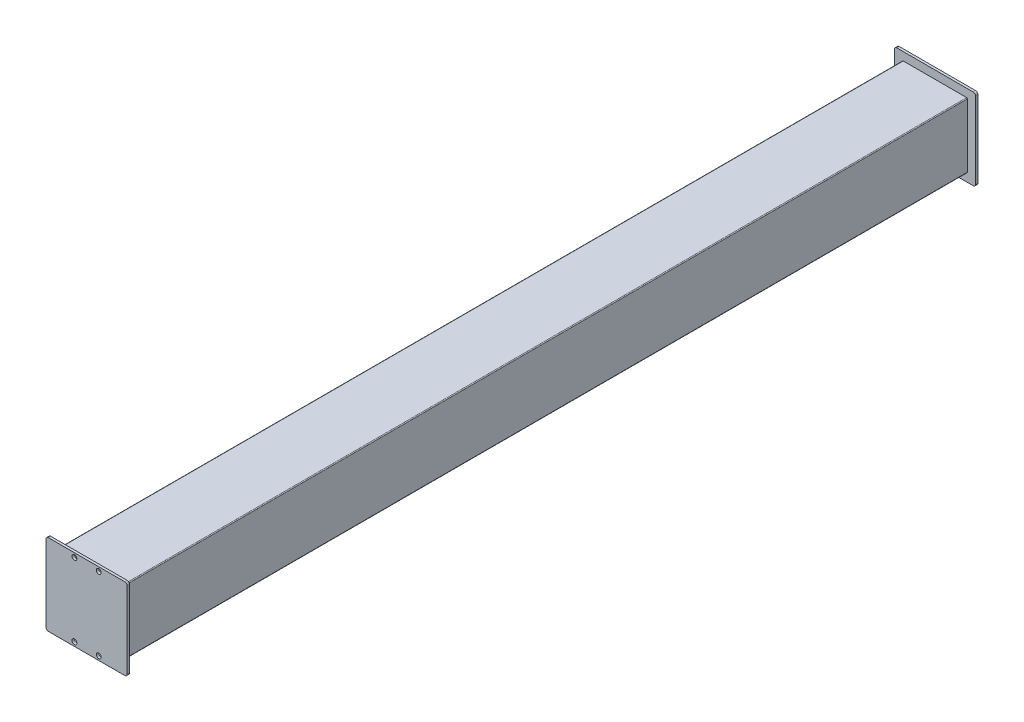
SolidWorks part; units mm, degrees
material "Alloy Steel"
ref_plane "Front Plane" through (0, 0, 0) normal (0, 0, 1) x (1, 0, 0)
ref_plane "Top Plane" through (0, 0, 0) normal (0, 1, 0) x (1, 0, 0)
ref_plane "Right Plane" through (0, 0, 0) normal (1, 0, 0) x (0, 0, -1)
sketch "Sketch2" plane through (0, 0, 0) normal (0, 0, 1) x (1, 0, 0)
  line L0 (-36.4, 36.4) -> (36.4, 36.4)
  line L1 (-40, -40) -> (40, -40)
  line L2 (-40, -40) -> (-40, 40)
  line L3 (-40, 40) -> (40, 40)
  line L4 (40, -40) -> (40, 40)
  line L5 (-40, -40) -> (40, 40) construction
  line L6 (-40, 40) -> (40, -40) construction
  line L7 (36.4, -36.4) -> (36.4, 36.4)
  line L8 (-36.4, -36.4) -> (36.4, -36.4)
  line L9 (-36.4, -36.4) -> (-36.4, 36.4)
  point P0 (0, 0)
  dimension "D1" = 80
  dimension "D2" = 80
  dimension "D3" = 3.6
extrude "Boss-Extrude1" add sketch "Sketch2" along normal blind 1042
fillet "Fillet1" radius 1 4 edges at (40, -40, 521) (-40, -40, 521) (40, 40, 521) (-40, 40, 521)
fillet "Fillet2" radius 1 4 edges at (36.4, -36.4, 521) (-36.4, -36.4, 521) (-36.4, 36.4, 521) (36.4, 36.4, 521)
sketch "Sketch3" plane through (0, 0, 1042) normal (0, 0, 1) x (1, 0, 0)
  line L1 (-50, -50) -> (50, -50)
  line L2 (-50, -50) -> (-50, 50)
  line L3 (-50, 50) -> (50, 50)
  line L4 (50, -50) -> (50, 50)
  line L5 (-50, -50) -> (50, 50) construction
  line L6 (-50, 50) -> (50, -50) construction
  point P0 (0, 0)
  dimension "D1" = 100
  dimension "D2" = 100
extrude "Boss-Extrude2" add sketch "Sketch3" along normal blind 3
fillet "Fillet3" radius 3 4 edges at (-50, -50, 1043.5) (50, -50, 1043.5) (50, 50, 1043.5) (-50, 50, 1043.5)
sketch "Sketch5" plane through (0, 0, 1042) normal (0, 0, -1) x (-1, 0, 0)
  line L0 (0, -50) -> (0, 50) construction
  line L1 (47, -50) -> (-47, -50) construction
  line L2 (-47, 50) -> (47, 50) construction
  line L3 (-50, 0) -> (50, 0) construction
  line L4 (-50, -47) -> (-50, 47) construction
  line L5 (50, 47) -> (50, -47) construction
  circle A0 centre (15, -45) radius 3
  circle A1 centre (-15, -45) radius 3
  circle A2 centre (15, 45) radius 3
  circle A3 centre (-15, 45) radius 3
  dimension "D1" = 5
  dimension "D2" = 5
  dimension "D3" = 6
  dimension "D4" = 15
  dimension "D5" = 15
extrude "Cut-Extrude1" cut sketch "Sketch5" against normal up to surface (3 mm away) up to face at (0, 0, 1045)
sketch "Sketch6" plane through (0, 0, 0) normal (0, 0, -1) x (-1, 0, 0)
  line L1 (-50, -50) -> (50, -50)
  line L2 (-50, -50) -> (-50, 50)
  line L3 (-50, 50) -> (50, 50)
  line L4 (50, -50) -> (50, 50)
  line L5 (-50, -50) -> (50, 50) construction
  line L6 (-50, 50) -> (50, -50) construction
  point P0 (0, 0)
  dimension "D1" = 100
  dimension "D2" = 100
extrude "Boss-Extrude3" add sketch "Sketch6" along normal blind 3
fillet "Fillet4" radius 3 4 edges at (50, -50, -1.5) (-50, -50, -1.5) (-50, 50, -1.5) (50, 50, -1.5)
